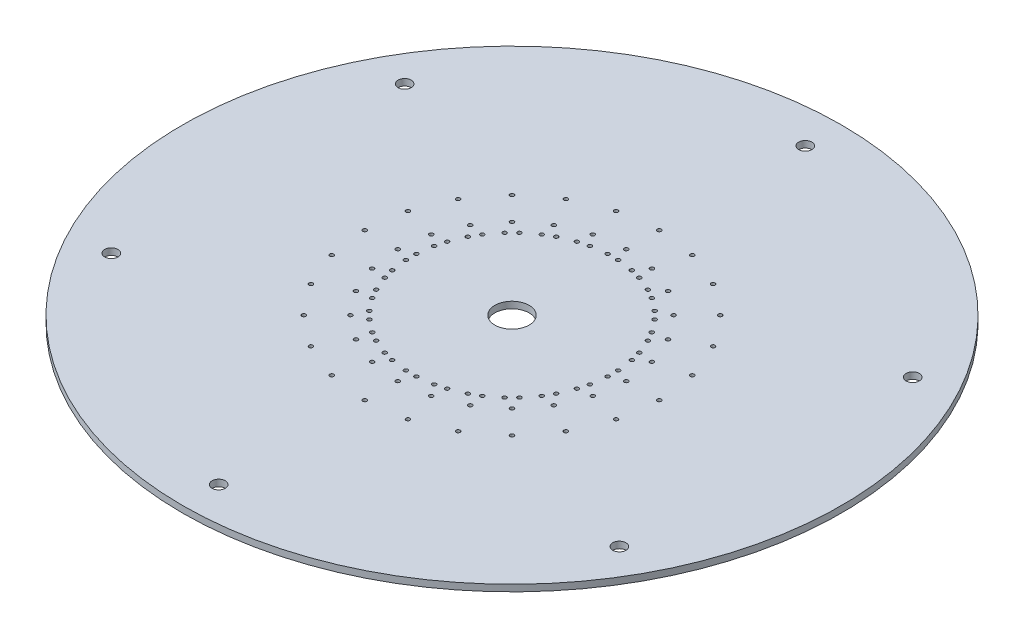
SolidWorks part; units mm, degrees
material "ABS PC"
ref_plane "Front Plane" through (0, 0, 0) normal (0, 0, 1) x (1, 0, 0)
ref_plane "Top Plane" through (0, 0, 0) normal (0, 1, 0) x (1, 0, 0)
ref_plane "Right Plane" through (0, 0, 0) normal (1, 0, 0) x (0, 0, -1)
sketch "Sketch1" plane through (0, 0, 0) normal (0, 1, 0) x (1, 0, 0)
  line L0 (0, 0) -> (0, 145.2031) construction
  line L1 (0, 0) -> (86.65, 0) construction
  circle A0 centre (0, 0) radius 250
  circle A1 centre (0, 0) radius 76.652 construction
  circle A2 centre (0, 76.652) radius 2.5 construction
  circle A3 centre (21.001, 74.9318) radius 2.5 construction
  circle A4 centre (40.8412, 67.8347) radius 2.5 construction
  circle A5 centre (58.1686, 55.8445) radius 2.5 construction
  circle A6 centre (71.8022, 39.7782) radius 2.5 construction
  circle A7 centre (80.813, 20.7307) radius 2.5 construction
  circle A8 centre (84.5868, 0) radius 2.5 construction
  circle A9 centre (82.8667, -21.001) radius 2.5 construction
  circle A10 centre (75.7696, -40.8412) radius 2.5 construction
  circle A11 centre (63.7794, -58.1686) radius 2.5 construction
  circle A12 centre (47.713, -71.8022) radius 2.5 construction
  circle A13 centre (28.6655, -80.813) radius 2.5 construction
  circle A14 centre (7.9349, -84.5868) radius 2.5 construction
  circle A15 centre (-13.0662, -82.8667) radius 2.5 construction
  circle A16 centre (-32.9064, -75.7696) radius 2.5 construction
  circle A17 centre (-50.2337, -63.7794) radius 2.5 construction
  circle A18 centre (-63.8673, -47.713) radius 2.5 construction
  circle A19 centre (-72.8781, -28.6655) radius 2.5 construction
  circle A20 centre (-76.652, -7.9349) radius 2.5 construction
  circle A21 centre (-74.9318, 13.0662) radius 2.5 construction
  circle A22 centre (-67.8347, 32.9064) radius 2.5 construction
  circle A23 centre (-55.8445, 50.2337) radius 2.5 construction
  circle A24 centre (-39.7782, 63.8673) radius 2.5 construction
  circle A25 centre (-20.7307, 72.8781) radius 2.5 construction
  circle A26 centre (-4, 76.5475) radius 1.5
  circle A27 centre (4, 76.5475) radius 1.5
  circle A28 centre (15.9483, 74.9745) radius 1.5
  circle A29 centre (23.6757, 72.904) radius 1.5
  circle A30 centre (34.8097, 68.2921) radius 1.5
  circle A31 centre (41.7379, 64.2921) radius 1.5
  circle A32 centre (51.2989, 56.9557) radius 1.5
  circle A33 centre (56.9557, 51.2989) radius 1.5
  circle A34 centre (64.2921, 41.7379) radius 1.5
  circle A35 centre (68.2921, 34.8097) radius 1.5
  circle A36 centre (72.904, 23.6757) radius 1.5
  circle A37 centre (74.9745, 15.9483) radius 1.5
  circle A38 centre (76.5475, 4) radius 1.5
  circle A39 centre (76.5475, -4) radius 1.5
  circle A40 centre (74.9745, -15.9483) radius 1.5
  circle A41 centre (72.904, -23.6757) radius 1.5
  circle A42 centre (68.2921, -34.8097) radius 1.5
  circle A43 centre (64.2921, -41.7379) radius 1.5
  circle A44 centre (56.9557, -51.2989) radius 1.5
  circle A45 centre (51.2989, -56.9557) radius 1.5
  circle A46 centre (41.7379, -64.2921) radius 1.5
  circle A47 centre (34.8097, -68.2921) radius 1.5
  circle A48 centre (23.6757, -72.904) radius 1.5
  circle A49 centre (15.9483, -74.9745) radius 1.5
  circle A50 centre (4, -76.5475) radius 1.5
  circle A51 centre (-4, -76.5475) radius 1.5
  circle A52 centre (-15.9483, -74.9745) radius 1.5
  circle A53 centre (-23.6757, -72.904) radius 1.5
  circle A54 centre (-34.8097, -68.2921) radius 1.5
  circle A55 centre (-41.7379, -64.2921) radius 1.5
  circle A56 centre (-51.2989, -56.9557) radius 1.5
  circle A57 centre (-56.9557, -51.2989) radius 1.5
  circle A58 centre (-64.2921, -41.7379) radius 1.5
  circle A59 centre (-68.2921, -34.8097) radius 1.5
  circle A60 centre (-72.904, -23.6757) radius 1.5
  circle A61 centre (-74.9745, -15.9483) radius 1.5
  circle A62 centre (-76.5475, -4) radius 1.5
  circle A63 centre (-76.5475, 4) radius 1.5
  circle A64 centre (-74.9745, 15.9483) radius 1.5
  circle A65 centre (-72.904, 23.6757) radius 1.5
  circle A66 centre (-68.2921, 34.8097) radius 1.5
  circle A67 centre (-64.2921, 41.7379) radius 1.5
  circle A68 centre (-56.9557, 51.2989) radius 1.5
  circle A69 centre (-51.2989, 56.9557) radius 1.5
  circle A70 centre (-41.7379, 64.2921) radius 1.5
  circle A71 centre (-34.8097, 68.2921) radius 1.5
  circle A72 centre (-23.6757, 72.904) radius 1.5
  circle A73 centre (-15.9483, 74.9745) radius 1.5
  circle A74 centre (0, 0) radius 13
  circle A75 centre (86.65, 0) radius 1.5
  circle A76 centre (111.65, 0) radius 1.5
  circle A77 centre (107.8456, -28.8971) radius 1.5
  circle A78 centre (96.6917, -55.825) radius 1.5
  circle A79 centre (78.9485, -78.9485) radius 1.5
  circle A80 centre (55.825, -96.6917) radius 1.5
  circle A81 centre (28.8971, -107.8456) radius 1.5
  circle A82 centre (0, -111.65) radius 1.5
  circle A83 centre (-28.8971, -107.8456) radius 1.5
  circle A84 centre (-55.825, -96.6917) radius 1.5
  circle A85 centre (-78.9485, -78.9485) radius 1.5
  circle A86 centre (-96.6917, -55.825) radius 1.5
  circle A87 centre (-107.8456, -28.8971) radius 1.5
  circle A88 centre (-111.65, 0) radius 1.5
  circle A89 centre (-107.8456, 28.8971) radius 1.5
  circle A90 centre (-96.6917, 55.825) radius 1.5
  circle A91 centre (-78.9485, 78.9485) radius 1.5
  circle A92 centre (-55.825, 96.6917) radius 1.5
  circle A93 centre (-28.8971, 107.8456) radius 1.5
  circle A94 centre (0, 111.65) radius 1.5
  circle A95 centre (28.8971, 107.8456) radius 1.5
  circle A96 centre (55.825, 96.6917) radius 1.5
  circle A97 centre (78.9485, 78.9485) radius 1.5
  circle A98 centre (96.6917, 55.825) radius 1.5
  circle A99 centre (107.8456, 28.8971) radius 1.5
  circle A100 centre (0, 0) radius 111.65 construction
  circle A101 centre (0, 0) radius 81.1 construction
  circle A103 centre (83.6975, -22.4267) radius 1.5
  circle A104 centre (75.0411, -43.325) radius 1.5
  circle A105 centre (61.2708, -61.2708) radius 1.5
  circle A106 centre (43.325, -75.0411) radius 1.5
  circle A107 centre (22.4267, -83.6975) radius 1.5
  circle A108 centre (0, -86.65) radius 1.5
  circle A109 centre (-22.4267, -83.6975) radius 1.5
  circle A110 centre (-43.325, -75.0411) radius 1.5
  circle A111 centre (-61.2708, -61.2708) radius 1.5
  circle A112 centre (-75.0411, -43.325) radius 1.5
  circle A113 centre (-83.6975, -22.4267) radius 1.5
  circle A114 centre (-86.65, 0) radius 1.5
  circle A115 centre (-83.6975, 22.4267) radius 1.5
  circle A116 centre (-75.0411, 43.325) radius 1.5
  circle A117 centre (-61.2708, 61.2708) radius 1.5
  circle A118 centre (-43.325, 75.0411) radius 1.5
  circle A119 centre (-22.4267, 83.6975) radius 1.5
  circle A120 centre (0, 86.65) radius 1.5
  circle A121 centre (22.4267, 83.6975) radius 1.5
  circle A122 centre (43.325, 75.0411) radius 1.5
  circle A123 centre (61.2708, 61.2708) radius 1.5
  circle A124 centre (75.0411, 43.325) radius 1.5
  circle A125 centre (83.6975, 22.4267) radius 1.5
  circle A126 centre (0, 222.5) radius 5
  circle A127 centre (192.6907, 111.25) radius 5
  circle A128 centre (192.6907, -111.25) radius 5
  circle A129 centre (0, -222.5) radius 5
  circle A130 centre (-192.6907, -111.25) radius 5
  circle A131 centre (-192.6907, 111.25) radius 5
  point P55 (3.9674, -3.9674)
  point P152 (0, 0)
  point P205 (0, 0)
  point P265 (0, 0)
  dimension "D1" = 500
  dimension "D2" = 5
  dimension "D4" = 8
  dimension "D5" = 3
  dimension "D7" = 26
  dimension "D8" = 86.65
  dimension "D9" = 3
  dimension "D10" = 222.5
  dimension "D11" = 24
  dimension "D12" = 223.3
  dimension "D13" = 162.2
  dimension "D14" = 10
  dimension "D3" = 24
  dimension "D6" = 24
  dimension "D15" = 6
extrude "Boss-Extrude1" add sketch "Sketch1" along normal mid plane 5
